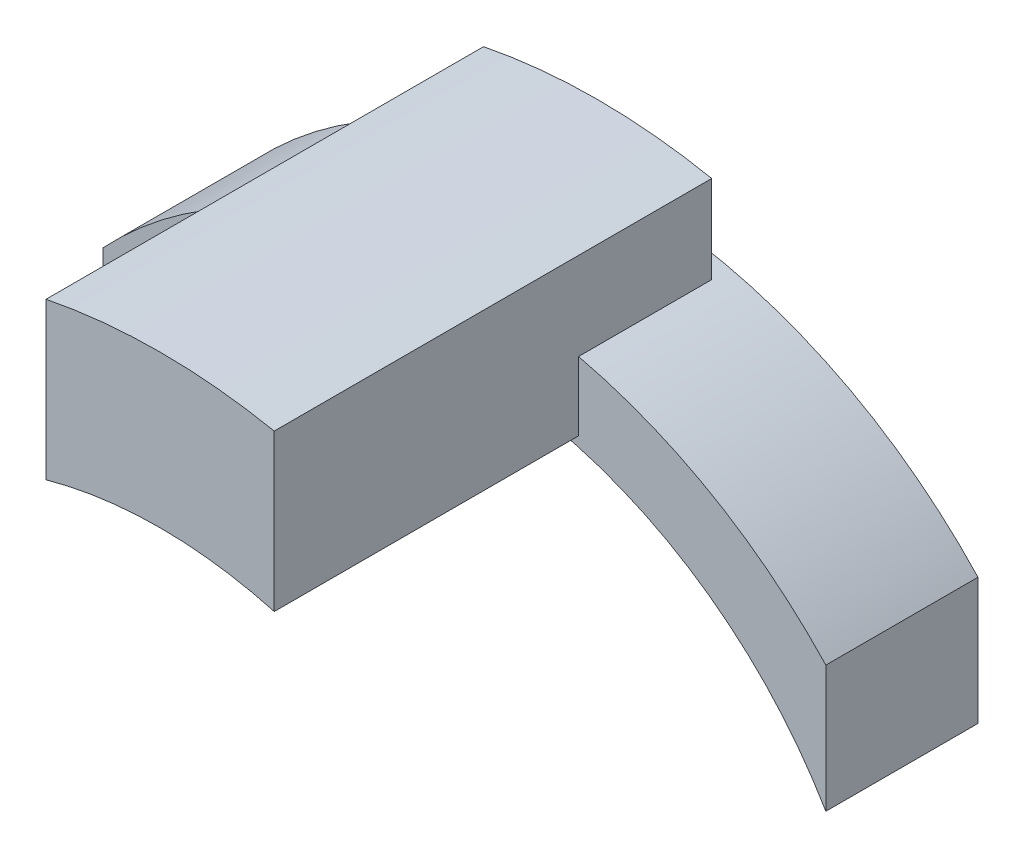
SolidWorks part; units mm, degrees
ref_plane "Front Plane" through (0, 0, 0) normal (0, 0, 1) x (1, 0, 0)
ref_plane "Top Plane" through (0, 0, 0) normal (0, 1, 0) x (1, 0, 0)
ref_plane "Right Plane" through (0, 0, 0) normal (1, 0, 0) x (0, 0, -1)
sketch "Sketch1" plane through (0, 0, 0) normal (0, 0, 1) x (1, 0, 0)
  line L0 (-19, 11.0905) -> (-19, 17.7482)
  line L1 (19, 17.7482) -> (19, 11.0905)
  arc A0 (19, 11.0905) -> (-19, 11.0905) centre (0, 0) ccw
  arc A1 (19, 17.7482) -> (-19, 17.7482) centre (0, 0) ccw
  dimension "D1" = 44
  dimension "D3" = 4
  dimension "D2" = 38
extrude "Extrude1" add sketch "Sketch1" along normal mid plane 8
sketch "Sketch2" plane through (0, 0, 4) normal (0, 0, -1) x (-1, 0, 0)
  line L0 (6, 21.6852) -> (6, 29.904)
  line L1 (-6, 29.904) -> (-6, 21.6852)
  arc A0 (6, 29.904) -> (-6, 29.904) centre (0, 0) ccw
  arc A2 (6, 21.6852) -> (-6, 21.6852) centre (0, 0) ccw
  arc A3 (19, 11.0905) -> (-19, 11.0905) centre (0, 0) ccw construction
  dimension "D2" = 8
  dimension "D3" = 0.5
  dimension "D1" = 12
extrude "Extrude2" add sketch "Sketch2" against normal blind 16 and the other way blind 7
